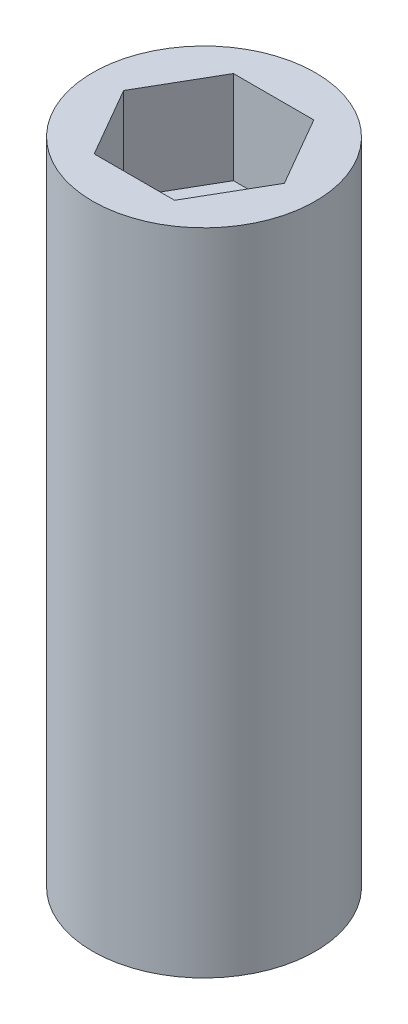
SolidWorks part; units mm, degrees
ref_plane "Front Plane" through (0, 0, 0) normal (0, 0, 1) x (1, 0, 0)
ref_plane "Top Plane" through (0, 0, 0) normal (0, 1, 0) x (1, 0, 0)
ref_plane "Right Plane" through (0, 0, 0) normal (1, 0, 0) x (0, 0, -1)
sketch "Sketch1" plane through (0, 0, 0) normal (0, 1, 0) x (1, 0, 0)
  circle A0 centre (0, 0) radius 1.2
  dimension "D1" = 2.4
extrude "Boss-Extrude1" add sketch "Sketch1" along normal blind 7
sketch "Sketch2" plane through (0, 7, 0) normal (0, 1, 0) x (1, 0, 0)
  line L1 (0.866, 0) -> (0.433, 0.75)
  line L2 (0.433, 0.75) -> (-0.433, 0.75)
  line L3 (-0.433, 0.75) -> (-0.866, 0)
  line L4 (-0.866, 0) -> (-0.433, -0.75)
  line L5 (-0.433, -0.75) -> (0.433, -0.75)
  line L6 (0.433, -0.75) -> (0.866, 0)
  circle A0 centre (0, 0) radius 0.75 construction
extrude "Cut-Extrude1" cut sketch "Sketch2" against normal blind 1
